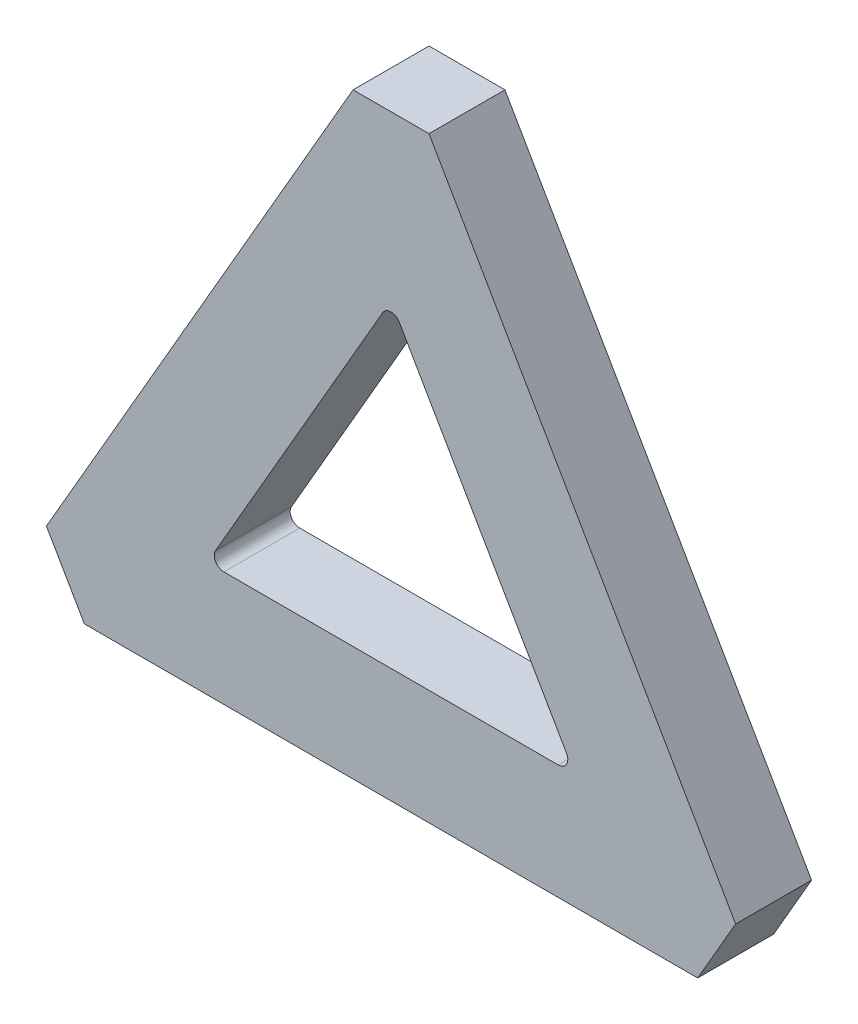
SolidWorks part; units mm, degrees
ref_plane "前基準面" through (0, 0, 0) normal (0, 0, 1) x (1, 0, 0)
ref_plane "上基準面" through (0, 0, 0) normal (0, 1, 0) x (1, 0, 0)
ref_plane "右基準面" through (0, 0, 0) normal (1, 0, 0) x (0, 0, -1)
sketch "Sketch1" plane through (0, 0, 0) normal (0, 0, 1) x (1, 0, 0)
  line L0 (0, 0) -> (-20, 0)
  line L1 (-20, 0) -> (-10, 17.3205)
  line L2 (-10, 17.3205) -> (0, 0)
  line L3 (-14.8038, 3) -> (-10, 11.3205)
  line L4 (-10, 11.3205) -> (-5.1962, 3)
  line L5 (-5.1962, 3) -> (-14.8038, 3)
  dimension "D1" = 20
  dimension "D2" = 3
extrude "Boss-Extrude1" add sketch "Sketch1" along normal blind 1.9844
chamfer "Chamfer2" distance 1.9844 1 edges at (-20, 0, 0.9922)
chamfer "Chamfer4" distance 1.9844 1 edges at (0, 0, 0.9922)
chamfer "Chamfer5" distance 1.9844 1 edges at (-10, 17.3205, 0.9922)
fillet "Fillet1" radius 0.25 3 edges at (-5.1962, 3, 0.9922) (-14.8038, 3, 0.9922) (-10, 11.3205, 0.9922)
